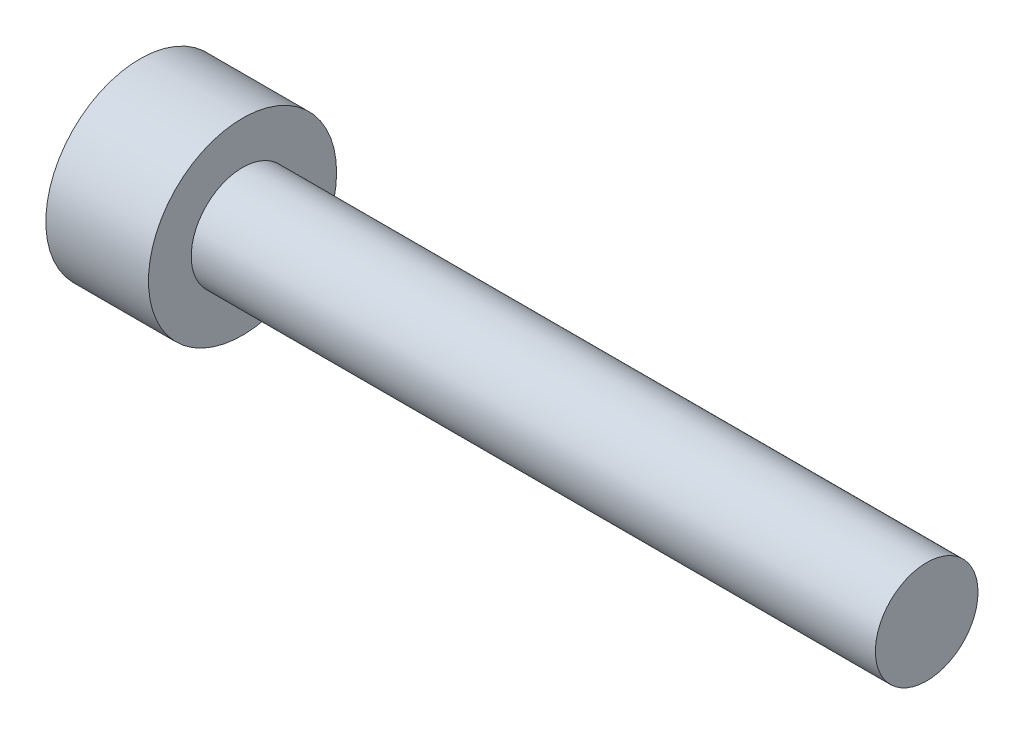
SolidWorks part; units mm, degrees
material "1.4000 (X6Cr13)"
ref_plane "Ebene vorne" through (0, 0, 0) normal (1, 0, 0) x (0, 1, 0)
ref_plane "Ebene oben" through (0, 0, 0) normal (0, 0, 1) x (0, 1, 0)
ref_plane "Ebene rechts" through (0, 0, 0) normal (0, 1, 0) x (-1, 0, 0)
sketch "Skizze1" plane through (0, 0, 0) normal (1, 0, 0) x (0, 1, 0)
  circle A0 centre (0, 0) radius 2.75
extrude "Aufsatz-Linear austragen1" add sketch "Skizze1" along normal blind 3 contours A0
sketch "Skizze2" plane through (0, 0, 0) normal (1, 0, 0) x (0, 1, 0)
  circle A0 centre (0, 0) radius 1.5
extrude "Aufsatz-Linear austragen2" add sketch "Skizze2" along normal blind 20 from offset 3
